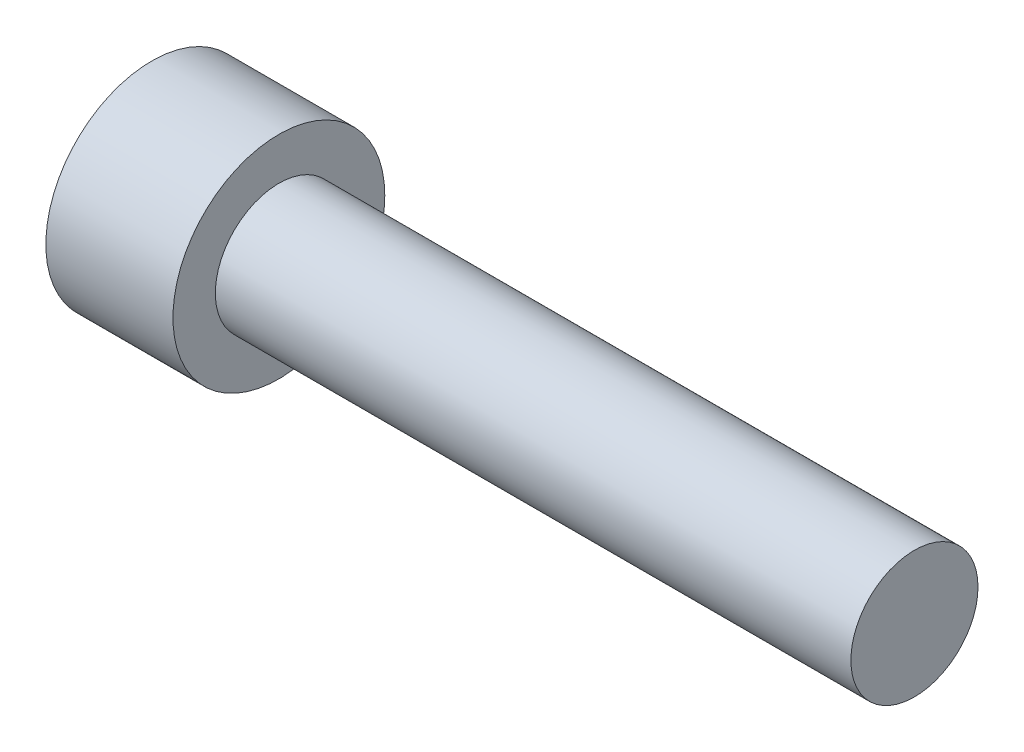
SolidWorks part; units mm, degrees
ref_plane "Front Plane" through (0, 0, 0) normal (0, 0, 1) x (1, 0, 0)
ref_plane "Top Plane" through (0, 0, 0) normal (0, 1, 0) x (1, 0, 0)
ref_plane "Right Plane" through (0, 0, 0) normal (1, 0, 0) x (0, 0, -1)
sketch "Sketch1" plane through (0, 0, 0) normal (0, 1, 0) x (1, 0, 0)
  line L0 (0, 0) -> (0, 2.5)
  line L1 (0, 2.5) -> (3, 2.5)
  line L2 (3, 2.5) -> (3, 1.5)
  line L3 (3, 1.5) -> (18, 1.5)
  line L4 (18, 1.5) -> (18, 0)
  line L5 (18, 0) -> (0, 0)
  dimension "D1" = 3
  dimension "D2" = 2.5
  dimension "D3" = 1.5
  dimension "D4" = 15
revolve "Revolve1" add sketch "Sketch1" angle 360 about L5
